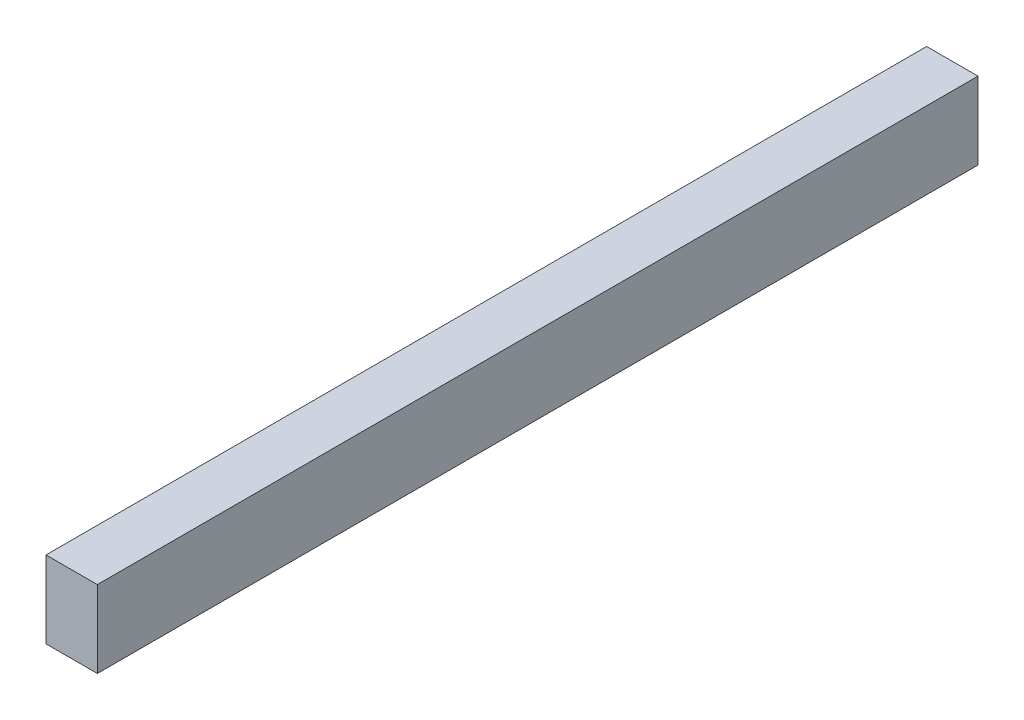
SolidWorks part; units mm, degrees
ref_plane "Front Plane" through (0, 0, 0) normal (0, 0, 1) x (1, 0, 0)
ref_plane "Top Plane" through (0, 0, 0) normal (0, 1, 0) x (1, 0, 0)
ref_plane "Right Plane" through (0, 0, 0) normal (1, 0, 0) x (0, 0, -1)
sketch "Sketch1" plane through (0, 0, 0) normal (0, 0, 1) x (1, 0, 0)
  line L1 (0, 0) -> (50.8, 0)
  line L2 (0, 0) -> (0, 76.2)
  line L3 (0, 76.2) -> (50.8, 76.2)
  line L4 (50.8, 0) -> (50.8, 76.2)
  dimension "D1" = 50.8
  dimension "D2" = 76.2
extrude "Boss-Extrude1" add sketch "Sketch1" along normal blind 871.22
